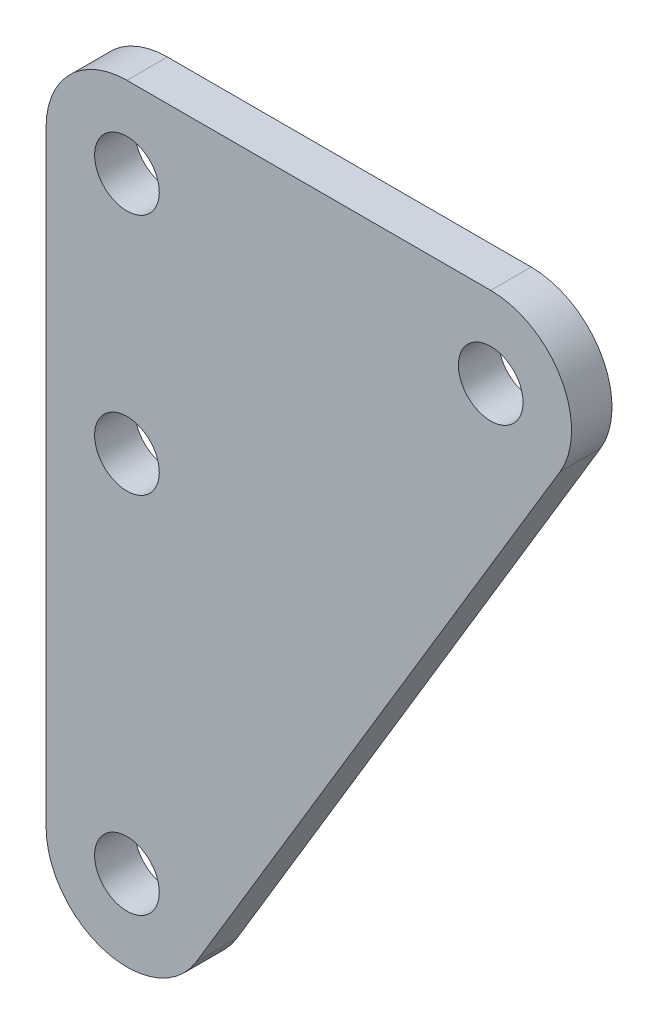
SolidWorks part; units mm, degrees
ref_plane "Front Plane" through (0, 0, 0) normal (0, 0, 1) x (1, 0, 0)
ref_plane "Top Plane" through (0, 0, 0) normal (0, 1, 0) x (1, 0, 0)
ref_plane "Right Plane" through (0, 0, 0) normal (1, 0, 0) x (0, 0, -1)
sketch "Sketch1" plane through (0, 0, 0) normal (0, 0, 1) x (1, 0, 0)
  line L0 (-10, -45) -> (-10, 30)
  line L1 (0, 40) -> (45, 40)
  line L2 (53.5749, 24.855) -> (8.5749, -50.145)
  circle A0 centre (0, 0) radius 4
  circle A1 centre (0, -45) radius 4
  circle A2 centre (0, 30) radius 4
  circle A3 centre (45, 30) radius 4
  arc A4 (-10, 30) -> (0, 40) centre (0, 30) cw
  arc A5 (45, 40) -> (53.5749, 24.855) centre (45, 30) cw
  arc A6 (8.5749, -50.145) -> (-10, -45) centre (0, -45) cw
  point P13 (0, 0)
  dimension "D5" = 8
  dimension "D6" = 10
  dimension "D1" = 45
  dimension "D2" = 45
  dimension "D3" = 30
  dimension "D4" = 0
extrude "Boss-Extrude1" add sketch "Sketch1" along normal blind 5
